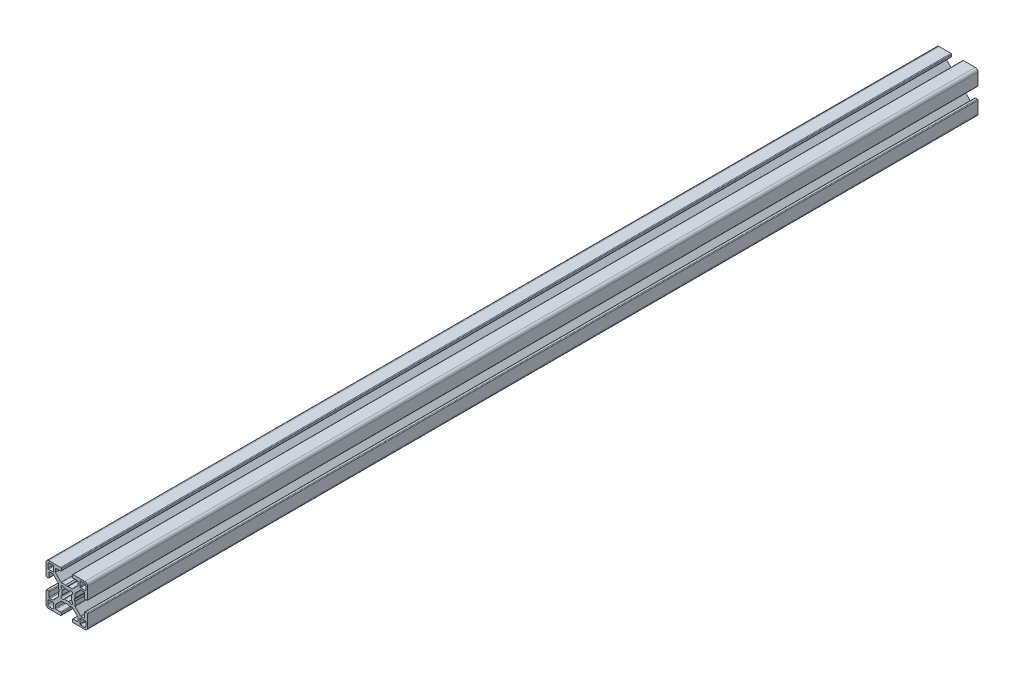
SolidWorks part; units mm, degrees
material "6105-T5 Aluminum"
ref_plane "Front Plane" through (0, 0, 0) normal (0, 0, 1) x (1, 0, 0)
ref_plane "Top Plane" through (0, 0, 0) normal (0, 1, 0) x (1, 0, 0)
ref_plane "Right Plane" through (0, 0, 0) normal (1, 0, 0) x (0, 0, -1)
sketch "Sketch1" plane through (0, 0, 0) normal (0, 0, 1) x (1, 0, 0)
  line L0 (9.5, -13.3189) -> (9.5, -9.88)
  line L1 (9.88, -9.5) -> (13.3189, -9.5)
  line L2 (13.6999, -9.881) -> (13.6999, -12.6999)
  line L3 (12.6999, -13.6999) -> (9.881, -13.6999)
  line L4 (-13.3189, -9.5) -> (-9.88, -9.5)
  line L5 (-9.5, -9.88) -> (-9.5, -13.3189)
  line L6 (-9.881, -13.6999) -> (-12.6999, -13.6999)
  line L7 (-13.6999, -12.6999) -> (-13.6999, -9.881)
  line L8 (-1.4942, -3.1981) -> (-2.4733, -3.9799)
  line L9 (-3.9799, -2.4733) -> (-3.1981, -1.4942)
  line L10 (-3.1981, 1.4942) -> (-3.9799, 2.4733)
  line L11 (-2.4733, 3.9799) -> (-1.4942, 3.1981)
  line L12 (1.4942, 3.1981) -> (2.4733, 3.9799)
  line L13 (3.9799, 2.4733) -> (3.1981, 1.4942)
  line L14 (3.1981, -1.4942) -> (3.9799, -2.4733)
  line L15 (2.4733, -3.9799) -> (1.4942, -3.1981)
  line L16 (-9.5, 13.3189) -> (-9.5, 9.88)
  line L17 (-9.88, 9.5) -> (-13.3189, 9.5)
  line L18 (-13.6999, 9.881) -> (-13.6999, 12.6999)
  line L19 (-12.6999, 13.6999) -> (-9.881, 13.6999)
  line L20 (9.881, 13.6999) -> (12.6999, 13.6999)
  line L21 (13.6999, 12.6999) -> (13.6999, 9.881)
  line L22 (13.3189, 9.5) -> (9.88, 9.5)
  line L23 (9.5, 9.88) -> (9.5, 13.3189)
  line L24 (12.7425, -4.5) -> (12.7425, -7.7325)
  line L25 (12.2428, -8.25) -> (10.2602, -8.25)
  line L26 (9.9066, -8.1035) -> (5.9811, -4.178)
  line L27 (5.8347, -3.8245) -> (5.8347, -1.0125)
  line L28 (5.8347, -1.0125) -> (5.3247, -0.0625)
  line L29 (5.3247, -0.0625) -> (5.8347, 0.8875)
  line L30 (5.8347, 0.8875) -> (5.8347, 3.8245)
  line L31 (5.9811, 4.178) -> (9.9066, 8.1035)
  line L32 (10.2602, 8.25) -> (12.2428, 8.25)
  line L33 (12.7425, 7.7325) -> (12.7425, 4.5)
  line L34 (13.2425, 4) -> (14.4999, 4)
  line L35 (14.9999, 4.5) -> (14.9999, 12.9999)
  line L36 (12.9999, 14.9999) -> (4.5, 14.9999)
  line L37 (4, 14.4999) -> (4, 13.2425)
  line L38 (4.5, 12.7425) -> (7.7325, 12.7425)
  line L39 (8.25, 12.2428) -> (8.25, 10.2602)
  line L40 (8.1035, 9.9066) -> (4.178, 5.9811)
  line L41 (3.8245, 5.8347) -> (0.95, 5.8347)
  line L42 (0.95, 5.8347) -> (0, 5.3247)
  line L43 (0, 5.3247) -> (-0.95, 5.8347)
  line L44 (-0.95, 5.8347) -> (-3.8245, 5.8347)
  line L45 (-4.178, 5.9811) -> (-8.1035, 9.9066)
  line L46 (-8.25, 10.2602) -> (-8.25, 12.2428)
  line L47 (-7.7325, 12.7425) -> (-4.5, 12.7425)
  line L48 (-4, 13.2425) -> (-4, 14.4999)
  line L49 (-4.5, 14.9999) -> (-12.9999, 14.9999)
  line L50 (-14.9999, 12.9999) -> (-14.9999, 4.5)
  line L51 (-14.4999, 4) -> (-13.2425, 4)
  line L52 (-12.7425, 4.5) -> (-12.7425, 7.7325)
  line L53 (-12.2428, 8.25) -> (-10.2602, 8.25)
  line L54 (-9.9066, 8.1035) -> (-5.9811, 4.178)
  line L55 (-5.8347, 3.8245) -> (-5.8347, 0.8875)
  line L56 (-5.8347, 0.8875) -> (-5.3247, -0.0625)
  line L57 (-5.3247, -0.0625) -> (-5.8347, -1.0125)
  line L58 (-5.8347, -1.0125) -> (-5.8347, -3.8245)
  line L59 (-5.9811, -4.178) -> (-9.9066, -8.1035)
  line L60 (-10.2602, -8.25) -> (-12.2428, -8.25)
  line L61 (-12.7425, -7.7325) -> (-12.7425, -4.5)
  line L62 (-13.2425, -4) -> (-14.4999, -4)
  line L63 (-14.9999, -4.5) -> (-14.9999, -12.9999)
  line L64 (-12.9999, -14.9999) -> (-4.5, -14.9999)
  line L65 (-4, -14.4999) -> (-4, -13.2425)
  line L66 (-4.5, -12.7425) -> (-7.7325, -12.7425)
  line L67 (-8.25, -12.2428) -> (-8.25, -10.2602)
  line L68 (-8.1035, -9.9066) -> (-4.178, -5.9811)
  line L69 (-3.8245, -5.8347) -> (-0.95, -5.8347)
  line L70 (-0.95, -5.8347) -> (0, -5.3247)
  line L71 (0, -5.3247) -> (0.95, -5.8347)
  line L72 (0.95, -5.8347) -> (3.8245, -5.8347)
  line L73 (4.178, -5.9811) -> (8.1035, -9.9066)
  line L74 (8.25, -10.2602) -> (8.25, -12.2428)
  line L75 (7.7325, -12.7425) -> (4.5, -12.7425)
  line L76 (4, -13.2425) -> (4, -14.4999)
  line L77 (4.5, -14.9999) -> (12.9999, -14.9999)
  line L78 (14.9999, -12.9999) -> (14.9999, -4.5)
  line L79 (14.4999, -4) -> (13.2425, -4)
  arc A0 (9.5, -13.3189) -> (9.881, -13.6999) centre (9.881, -13.3189) ccw
  arc A1 (9.88, -9.5) -> (9.5, -9.88) centre (9.88, -9.88) ccw
  arc A2 (13.6999, -9.881) -> (13.3189, -9.5) centre (13.3189, -9.881) ccw
  arc A3 (12.6999, -13.6999) -> (13.6999, -12.6999) centre (12.6999, -12.6999) ccw
  arc A4 (-13.3189, -9.5) -> (-13.6999, -9.881) centre (-13.3189, -9.881) ccw
  arc A5 (-9.5, -9.88) -> (-9.88, -9.5) centre (-9.88, -9.88) ccw
  arc A6 (-9.881, -13.6999) -> (-9.5, -13.3189) centre (-9.881, -13.3189) ccw
  arc A7 (-13.6999, -12.6999) -> (-12.6999, -13.6999) centre (-12.6999, -12.6999) ccw
  arc A8 (-1.4942, -3.1981) -> (1.4942, -3.1981) centre (0, 0) ccw
  arc A9 (-3.9799, -2.4733) -> (-2.4733, -3.9799) centre (-3.1422, -3.1422) ccw
  arc A10 (-3.1981, 1.4942) -> (-3.1981, -1.4942) centre (0, 0) ccw
  arc A11 (-2.4733, 3.9799) -> (-3.9799, 2.4733) centre (-3.1422, 3.1422) ccw
  arc A12 (1.4942, 3.1981) -> (-1.4942, 3.1981) centre (0, 0) ccw
  arc A13 (3.9799, 2.4733) -> (2.4733, 3.9799) centre (3.1422, 3.1422) ccw
  arc A14 (3.1981, -1.4942) -> (3.1981, 1.4942) centre (0, 0) ccw
  arc A15 (2.4733, -3.9799) -> (3.9799, -2.4733) centre (3.1422, -3.1422) ccw
  arc A16 (-9.5, 13.3189) -> (-9.881, 13.6999) centre (-9.881, 13.3189) ccw
  arc A17 (-9.88, 9.5) -> (-9.5, 9.88) centre (-9.88, 9.88) ccw
  arc A18 (-13.6999, 9.881) -> (-13.3189, 9.5) centre (-13.3189, 9.881) ccw
  arc A19 (-12.6999, 13.6999) -> (-13.6999, 12.6999) centre (-12.6999, 12.6999) ccw
  arc A20 (9.881, 13.6999) -> (9.5, 13.3189) centre (9.881, 13.3189) ccw
  arc A21 (13.6999, 12.6999) -> (12.6999, 13.6999) centre (12.6999, 12.6999) ccw
  arc A22 (13.3189, 9.5) -> (13.6999, 9.881) centre (13.3189, 9.881) ccw
  arc A23 (9.5, 9.88) -> (9.88, 9.5) centre (9.88, 9.88) ccw
  arc A24 (13.2425, -4) -> (12.7425, -4.5) centre (13.2425, -4.5) ccw
  arc A25 (12.2428, -8.25) -> (12.7425, -7.7325) centre (12.2428, -7.75) ccw
  arc A26 (9.9066, -8.1035) -> (10.2602, -8.25) centre (10.2602, -7.75) ccw
  arc A27 (5.8347, -3.8245) -> (5.9811, -4.178) centre (6.3347, -3.8245) ccw
  arc A28 (5.9811, 4.178) -> (5.8347, 3.8245) centre (6.3347, 3.8245) ccw
  arc A29 (10.2602, 8.25) -> (9.9066, 8.1035) centre (10.2602, 7.75) ccw
  arc A30 (12.7425, 7.7325) -> (12.2428, 8.25) centre (12.2428, 7.75) ccw
  arc A31 (12.7425, 4.5) -> (13.2425, 4) centre (13.2425, 4.5) ccw
  arc A32 (14.4999, 4) -> (14.9999, 4.5) centre (14.4999, 4.5) ccw
  arc A33 (14.9999, 12.9999) -> (12.9999, 14.9999) centre (12.9999, 12.9999) ccw
  arc A34 (4.5, 14.9999) -> (4, 14.4999) centre (4.5, 14.4999) ccw
  arc A35 (4, 13.2425) -> (4.5, 12.7425) centre (4.5, 13.2425) ccw
  arc A36 (8.25, 12.2428) -> (7.7325, 12.7425) centre (7.75, 12.2428) ccw
  arc A37 (8.1035, 9.9066) -> (8.25, 10.2602) centre (7.75, 10.2602) ccw
  arc A38 (3.8245, 5.8347) -> (4.178, 5.9811) centre (3.8245, 6.3347) ccw
  arc A39 (-4.178, 5.9811) -> (-3.8245, 5.8347) centre (-3.8245, 6.3347) ccw
  arc A40 (-8.25, 10.2602) -> (-8.1035, 9.9066) centre (-7.75, 10.2602) ccw
  arc A41 (-7.7325, 12.7425) -> (-8.25, 12.2428) centre (-7.75, 12.2428) ccw
  arc A42 (-4.5, 12.7425) -> (-4, 13.2425) centre (-4.5, 13.2425) ccw
  arc A43 (-4, 14.4999) -> (-4.5, 14.9999) centre (-4.5, 14.4999) ccw
  arc A44 (-12.9999, 14.9999) -> (-14.9999, 12.9999) centre (-12.9999, 12.9999) ccw
  arc A45 (-14.9999, 4.5) -> (-14.4999, 4) centre (-14.4999, 4.5) ccw
  arc A46 (-13.2425, 4) -> (-12.7425, 4.5) centre (-13.2425, 4.5) ccw
  arc A47 (-12.2428, 8.25) -> (-12.7425, 7.7325) centre (-12.2428, 7.75) ccw
  arc A48 (-9.9066, 8.1035) -> (-10.2602, 8.25) centre (-10.2602, 7.75) ccw
  arc A49 (-5.8347, 3.8245) -> (-5.9811, 4.178) centre (-6.3347, 3.8245) ccw
  arc A50 (-5.9811, -4.178) -> (-5.8347, -3.8245) centre (-6.3347, -3.8245) ccw
  arc A51 (-10.2602, -8.25) -> (-9.9066, -8.1035) centre (-10.2602, -7.75) ccw
  arc A52 (-12.7425, -7.7325) -> (-12.2428, -8.25) centre (-12.2428, -7.75) ccw
  arc A53 (-12.7425, -4.5) -> (-13.2425, -4) centre (-13.2425, -4.5) ccw
  arc A54 (-14.4999, -4) -> (-14.9999, -4.5) centre (-14.4999, -4.5) ccw
  arc A55 (-14.9999, -12.9999) -> (-12.9999, -14.9999) centre (-12.9999, -12.9999) ccw
  arc A56 (-4.5, -14.9999) -> (-4, -14.4999) centre (-4.5, -14.4999) ccw
  arc A57 (-4, -13.2425) -> (-4.5, -12.7425) centre (-4.5, -13.2425) ccw
  arc A58 (-8.25, -12.2428) -> (-7.7325, -12.7425) centre (-7.75, -12.2428) ccw
  arc A59 (-8.1035, -9.9066) -> (-8.25, -10.2602) centre (-7.75, -10.2602) ccw
  arc A60 (-3.8245, -5.8347) -> (-4.178, -5.9811) centre (-3.8245, -6.3347) ccw
  arc A61 (4.178, -5.9811) -> (3.8245, -5.8347) centre (3.8245, -6.3347) ccw
  arc A62 (8.25, -10.2602) -> (8.1035, -9.9066) centre (7.75, -10.2602) ccw
  arc A63 (7.7325, -12.7425) -> (8.25, -12.2428) centre (7.75, -12.2428) ccw
  arc A64 (4.5, -12.7425) -> (4, -13.2425) centre (4.5, -13.2425) ccw
  arc A65 (4, -14.4999) -> (4.5, -14.9999) centre (4.5, -14.4999) ccw
  arc A66 (12.9999, -14.9999) -> (14.9999, -12.9999) centre (12.9999, -12.9999) ccw
  arc A67 (14.9999, -4.5) -> (14.4999, -4) centre (14.4999, -4.5) ccw
extrude "Extrude1" add sketch "Sketch1" against normal blind 642
